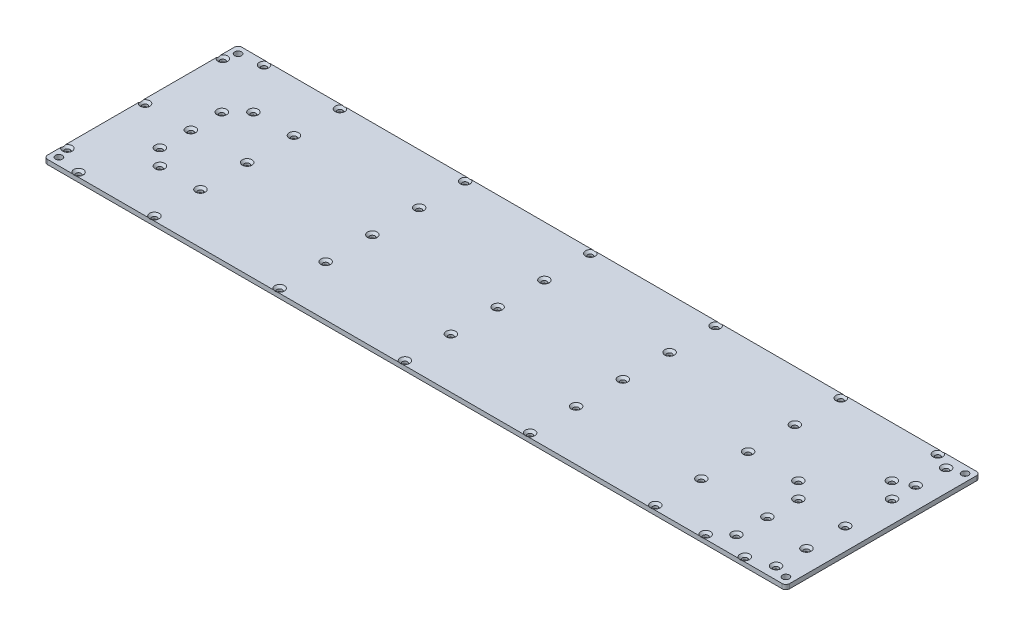
SolidWorks part; units mm, degrees
ref_plane "Front Plane" through (0, 0, 0) normal (0, 0, 1) x (1, 0, 0)
ref_plane "Top Plane" through (0, 0, 0) normal (0, 1, 0) x (1, 0, 0)
ref_plane "Right Plane" through (0, 0, 0) normal (1, 0, 0) x (0, 0, -1)
sketch "Sketch1" plane through (0, 0, 0) normal (0, 1, 0) x (1, 0, 0)
  line L1 (-244.475, 64) -> (244.475, 64)
  line L2 (-244.475, 64) -> (-244.475, -64)
  line L3 (-244.475, -64) -> (244.475, -64)
  line L4 (244.475, 64) -> (244.475, -64)
  line L5 (-244.475, 64) -> (244.475, -64) construction
  line L6 (-244.475, -64) -> (244.475, 64) construction
  point P0 (0, 0)
  dimension "D1" = 128
  dimension "D2" = 488.95
extrude "Boss-Extrude1" add sketch "Sketch1" along normal blind 3
hole_wizard "M4 Clearance Hole1" positions "Sketch2" profile "Sketch3" hole size "M4" standard "ANSI Metric"
sketch "Sketch2" plane through (0, 3, 0) normal (0, 1, 0) x (1, 0, 0)
  line L0 (239.475, 59) -> (239.475, -59) construction
  line L1 (239.475, -59) -> (-239.475, -59) construction
  line L2 (-239.475, -59) -> (-239.475, 59) construction
  line L3 (-239.475, 59) -> (239.475, 59) construction
  line L6 (244.475, 64) -> (-244.475, 64) construction
  line L7 (-244.475, 64) -> (-244.475, -64) construction
  line L8 (-244.475, -64) -> (244.475, -64) construction
  line L9 (244.475, -64) -> (244.475, 64) construction
  point P0 (-239.475, 59)
  point P2 (-239.475, -59)
  point P4 (239.475, -59)
  point P6 (239.475, 59)
  dimension "D1" = 5
  dimension "D2" = 5
  dimension "D3" = 5
  dimension "D4" = 5
sketch "Sketch3" plane through (-239.475, 3, -59) normal (1, 0, 0) x (0, 0, 1)
  line L0 (0, 0) -> (0, 18.7319)
  line L1 (0, 18.7319) -> (2.25, 17.38)
  line L2 (2.25, 17.38) -> (2.25, 0)
  line L5 (2.25, 0) -> (0, 0)
  line L10 (0, 18.7319) -> (-2.25, 17.38) construction
  line L11 (0, -6.35) -> (0, 107.95) construction
  dimension "Hole Dia." = 4.5
  dimension "Hole Depth" = 17.38
  dimension "Drill Angle" = 118
fillet "Fillet1" radius 2.5 4 edges at (244.475, 1.5, -64) (244.475, 1.5, 64) (-244.475, 1.5, -64) (-244.475, 1.5, 64)
hole_wizard "CSK for M3 Flat Head Machine Screw1" positions "Sketch4" profile "Sketch5" countersink size "M3" standard "ANSI Metric"
sketch "Sketch4" plane through (0, 3, 0) normal (0, 1, 0) x (1, 0, 0)
  point P2 (229.975, -56)
  point P7 (229.975, -36)
  point P12 (229.975, -10.4)
  point P17 (229.975, 20.4)
  point P24 (219.475, 30.8)
  point P31 (229.975, 56)
  point P36 (155.525, 61.1)
  point P51 (188.675, -61.1)
  point P54 (199.075, -51.2)
  point P57 (199.075, -30.8)
  point P60 (229.975, 36)
  point P63 (219.475, 61.1)
  point P66 (155.525, 30.8)
  point P69 (73.025, 30.8)
  point P72 (73.025, 61.1)
  point P75 (-9.475, 30.8)
  point P78 (-9.475, 61.1)
  point P81 (-91.975, 61.1)
  point P84 (-91.975, 30.8)
  point P87 (214.475, -61.1)
  point P90 (155.525, -61.1)
  point P93 (155.525, -30.8)
  point P96 (155.525, 0)
  point P99 (188.675, 0)
  point P102 (199.075, -10.4)
  point P106 (73.025, -30.8)
  point P109 (73.025, -61.1)
  point P112 (73.025, 0)
  point P115 (-91.975, -30.8)
  point P118 (-91.975, 0)
  point P122 (-91.975, -61.1)
  point P125 (-9.475, 0)
  point P128 (-9.475, -30.8)
  point P131 (-9.475, -61.1)
  point P134 (-201.175, 30.8)
  point P137 (-174.475, 30.8)
  point P140 (-174.475, 0)
  point P143 (-174.475, -30.8)
  point P146 (-174.475, -61.1)
  point P149 (-201.175, -30.8)
  point P152 (-211.575, -20.4)
  point P155 (-211.575, 0)
  point P158 (-211.575, 20.4)
  point P161 (-241.725, 51.2)
  point P164 (-241.725, 0)
  point P167 (-241.725, -51.2)
  point P170 (-224.475, -61.1)
  point P173 (-174.475, 61.1)
  point P176 (-224.475, 61.1)
sketch "Sketch5" plane through (229.975, 3, 56) normal (1, 0, 0) x (0, 0, 1)
  line L0 (0, 0) -> (0, 11.0215)
  line L1 (0, 11.0215) -> (1.7, 10)
  line L2 (1.7, 10) -> (1.7, 1.45)
  line L3 (1.7, 1.45) -> (3.15, 0)
  line L5 (3.15, 0) -> (0, 0)
  line L6 (-1.7, 1.45) -> (-3.15, 0) construction
  line L10 (0, 11.0215) -> (-1.7, 10) construction
  line L11 (0, -6.35) -> (0, 107.95) construction
  dimension "Hole Dia." = 3.4
  dimension "Hole Depth" = 10
  dimension "Near C'Sink Dia." = 6.3
  dimension "Near C'Sink Angle" = 90
  dimension "Drill Angle" = 118
